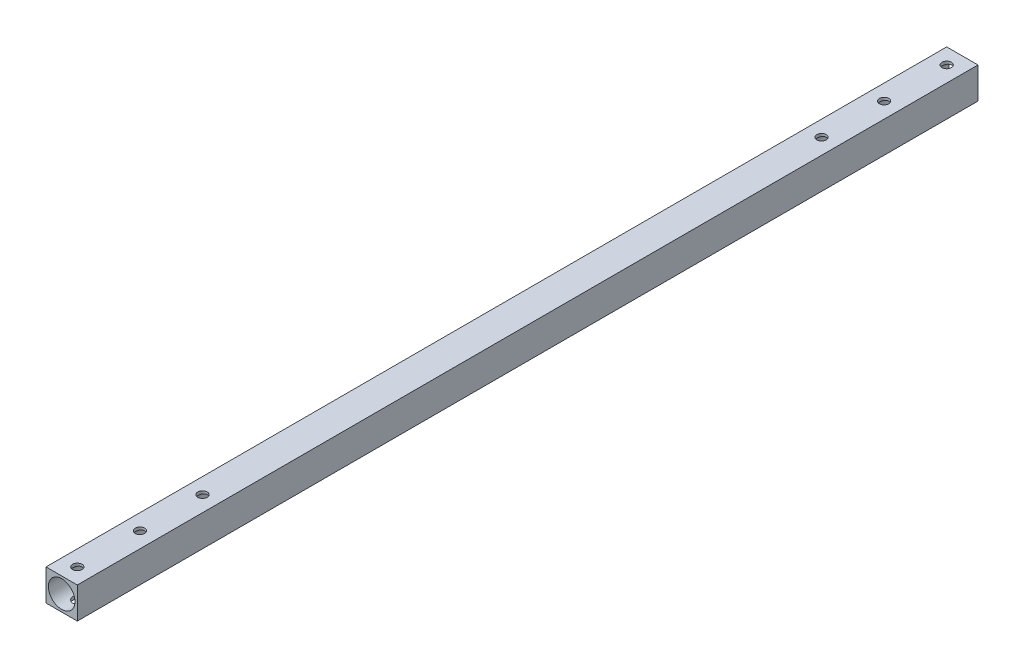
SolidWorks part; units mm, degrees
material "Thornel VCB-20 Carbon Cloth"
ref_plane "Front Plane" through (0, 0, 0) normal (0, 0, 1) x (1, 0, 0)
ref_plane "Top Plane" through (0, 0, 0) normal (0, 1, 0) x (1, 0, 0)
ref_plane "Right Plane" through (0, 0, 0) normal (1, 0, 0) x (0, 0, -1)
sketch "Sketch1" plane through (0, 0, 0) normal (0, 0, 1) x (1, 0, 0)
  line L1 (-5, -5) -> (5, -5)
  line L2 (-5, -5) -> (-5, 5)
  line L3 (-5, 5) -> (5, 5)
  line L4 (5, -5) -> (5, 5)
  line L5 (-5, -5) -> (5, 5) construction
  line L6 (-5, 5) -> (5, -5) construction
  circle A0 centre (0, 0) radius 4.25
  point P0 (0, 0)
  dimension "D3" = 8.5
  dimension "D1" = 10
  dimension "D2" = 10
extrude "Boss-Extrude1" add sketch "Sketch1" along normal blind 287.8
sketch "Sketch2" plane through (0, 5, 0) normal (0, 1, 0) x (1, 0, 0)
  line L0 (0, 0) -> (0, -5) construction
  line L1 (5, 0) -> (-5, 0) construction
  line L2 (0, -5) -> (0, -25) construction
  line L3 (0, -25) -> (0, -45) construction
  line L4 (0, -287.8) -> (0, -282.8) construction
  line L5 (5, -287.8) -> (-5, -287.8) construction
  line L6 (0, -282.8) -> (0, -262.8) construction
  line L7 (0, -262.8) -> (0, -242.8) construction
  circle A0 centre (0, -5) radius 1.5
  circle A1 centre (0, -25) radius 1.5
  circle A2 centre (0, -45) radius 1.5
  circle A3 centre (0, -282.8) radius 1.5
  circle A4 centre (0, -262.8) radius 1.5
  circle A5 centre (0, -242.8) radius 1.5
  dimension "D3" = 3
  dimension "D6" = 3
  dimension "D1" = 20
  dimension "D2" = 5
  dimension "D4" = 20
  dimension "D5" = 5
extrude "Cut-Extrude1" cut sketch "Sketch2" against normal through all
